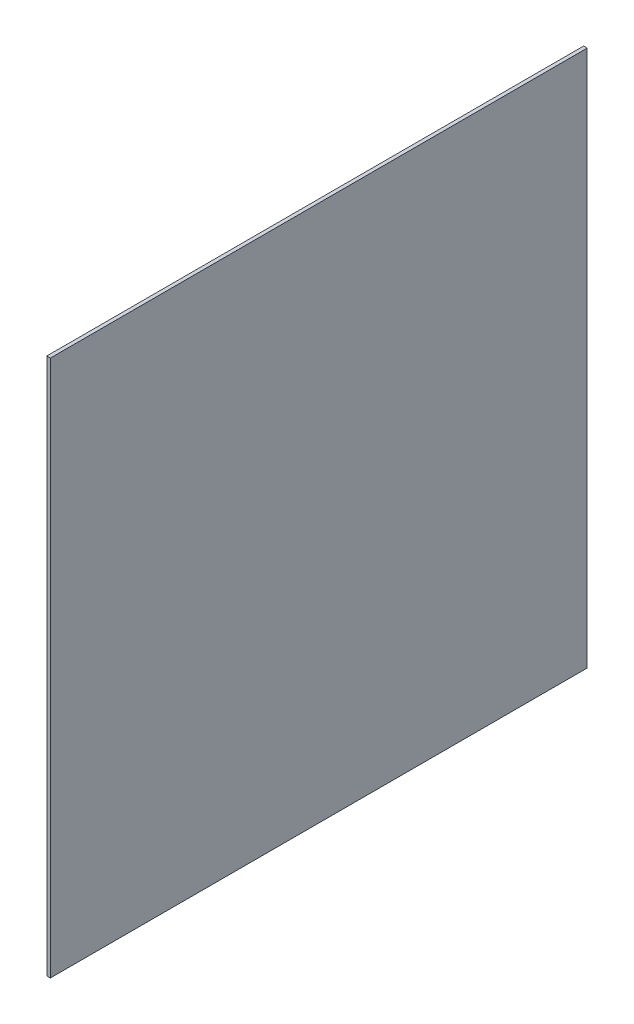
SolidWorks part; units mm, degrees
ref_plane "Plan de face" through (0, 0, 0) normal (0, 0, 1) x (1, 0, 0)
ref_plane "Plan de dessus" through (0, 0, 0) normal (0, 1, 0) x (1, 0, 0)
ref_plane "Plan de droite" through (0, 0, 0) normal (1, 0, 0) x (0, 0, -1)
sketch "Esquisse1" plane through (0, 0, 0) normal (0, 0, 1) x (1, 0, 0)
  point P0 (-20, 0)
  dimension "D1" = 20
sketch3d "Esquisse3D1"
  line L1 (-20, 1121.2893, 777.275) -> (-20, 1121.2893, -722.725)
  line L2 (-20, 1121.2893, 777.275) -> (-20, -378.7107, 777.275)
  line L3 (-20, -378.7107, 777.275) -> (-20, -378.7107, -722.725)
  line L4 (-20, 1121.2893, -722.725) -> (-20, -378.7107, -722.725)
  dimension "D1" = 1500
  dimension "D2" = 1500
extrude "Boss.-Extru.2" add sketch "Esquisse3D1" along direction (1, 0, 0) on the side of the normal blind 10 contours L2 L1 L4 L3
